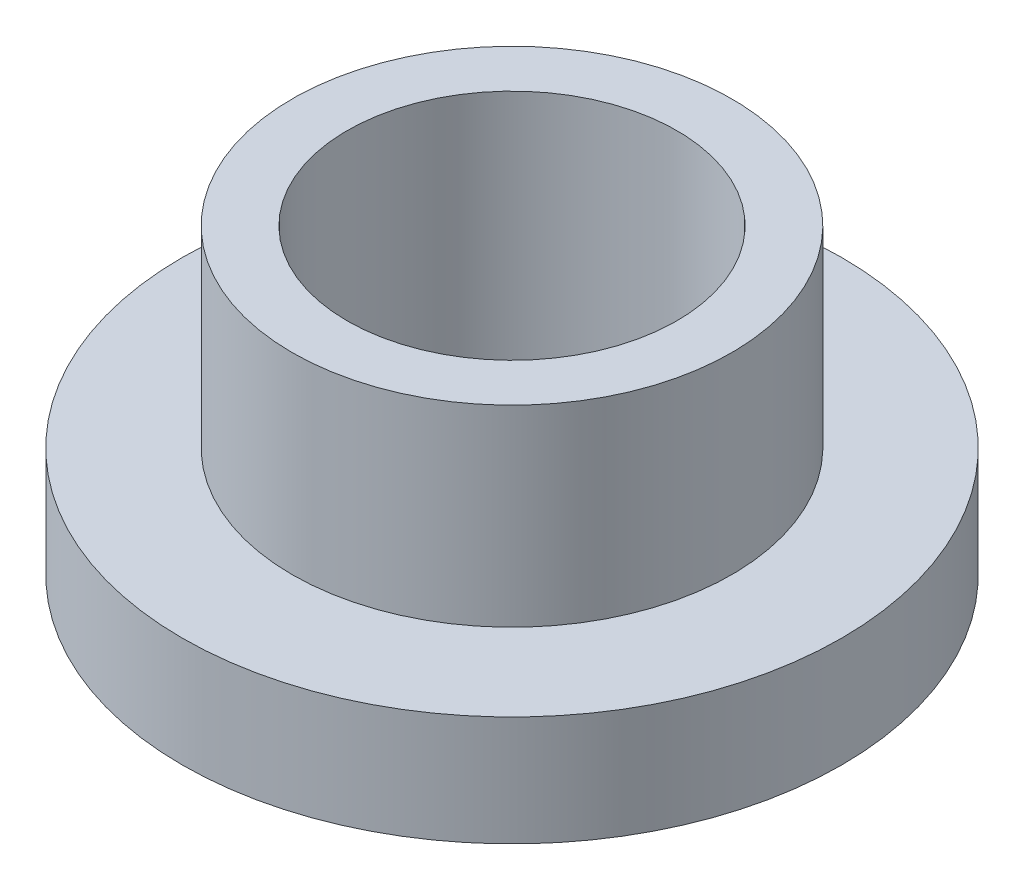
SolidWorks part; units mm, degrees
ref_plane "Front Plane" through (0, 0, 0) normal (0, 0, 1) x (1, 0, 0)
ref_plane "Top Plane" through (0, 0, 0) normal (0, 1, 0) x (1, 0, 0)
ref_plane "Right Plane" through (0, 0, 0) normal (1, 0, 0) x (0, 0, -1)
sketch "Sketch1" plane through (0, 0, 0) normal (0, 1, 0) x (1, 0, 0)
  circle A0 centre (0, 0) radius 6
  dimension "D1" = 12
extrude "Boss-Extrude1" add sketch "Sketch1" along normal mid plane 2
sketch "Sketch2" plane through (0, 1, 0) normal (0, 1, 0) x (1, 0, 0)
  circle A0 centre (0, 0) radius 4
  circle A1 centre (0, 0) radius 6 construction
  dimension "D1" = 8
extrude "Boss-Extrude2" add sketch "Sketch2" along normal blind 3.5
sketch "Sketch3" plane through (0, 4.5, 0) normal (0, 1, 0) x (1, 0, 0)
  circle A0 centre (0, 0) radius 3
  circle A1 centre (0, 0) radius 4 construction
  dimension "D1" = 6
extrude "Cut-Extrude1" cut sketch "Sketch3" against normal through all
